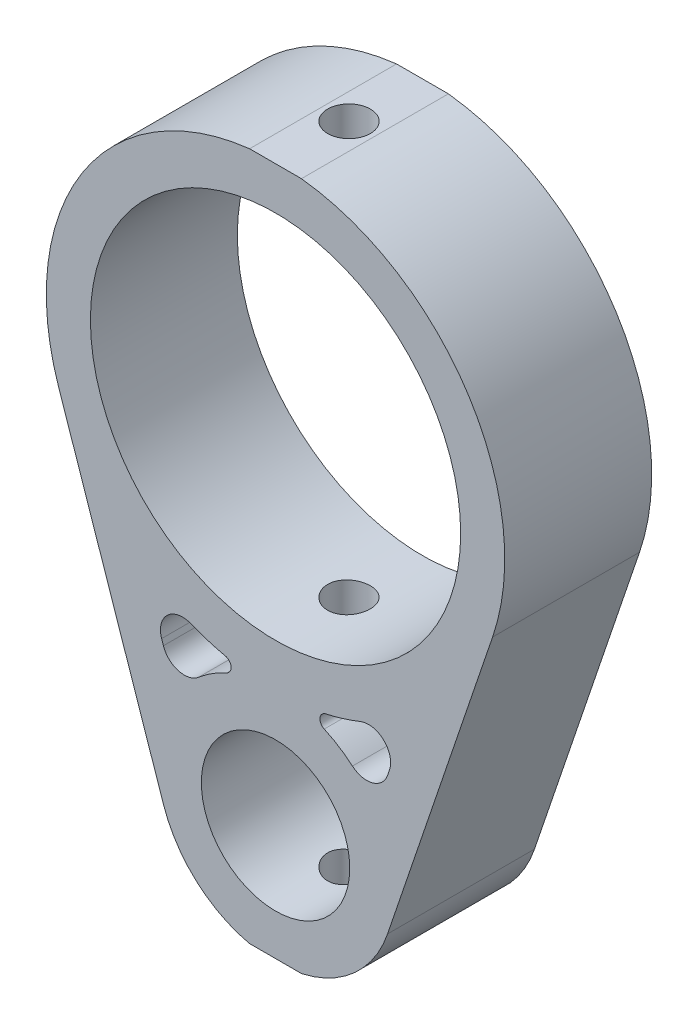
SolidWorks part; units mm, degrees
material "ABS"
ref_plane "前视基准面" through (0, 0, 0) normal (0, 0, 1) x (1, 0, 0)
ref_plane "上视基准面" through (0, 0, 0) normal (0, 1, 0) x (1, 0, 0)
ref_plane "右视基准面" through (0, 0, 0) normal (1, 0, 0) x (0, 0, -1)
sketch "草图1" plane through (0, 0, 0) normal (0, 0, 1) x (1, 0, 0)
  line L0 (0, 0) -> (0, -23.5) construction
  line L3 (-1.4149, -15.5357) -> (-1.4149, -15.5753)
  line L5 (1.4034, -15.5367) -> (1.4034, -15.5733)
  circle A0 centre (0, 0) radius 12.6
  arc A1 (1.4034, -15.5367) -> (-1.4149, -15.5357) centre (0, 0) ccw
  circle A2 centre (0, -23.5) radius 5.05
  arc A3 (-1.4149, -15.5753) -> (1.4034, -15.5733) centre (0, -23.5) ccw
  dimension "D1" = 25.2
  dimension "D2" = 3
  dimension "D3" = 10.1
  dimension "D4" = 3
  dimension "D5" = 23.5
extrude "凸台-拉伸1" add sketch "草图1" along normal blind 10
sketch "草图2" plane through (0, 0, 10) normal (0, 0, 1) x (1, 0, 0)
  line L0 (-14.773, -5.0119) -> (-7.6232, -26.0863)
  line L1 (-7.7529, -16.3662) -> (-7.6306, -16.7268)
  line L2 (0, 0) -> (0, -13.5175) construction
  line L3 (-4.1036, -15.0506) -> (-3.4583, -15.2119)
  line L4 (-14.773, -5.0119) -> (-5.3112, -13.2523)
  line L5 (-5.3112, -13.2523) -> (0, -13.5175)
  line L7 (0, -17.3992) -> (-5.929, -20.2543)
  line L8 (-5.929, -20.2543) -> (-7.6232, -26.0863)
  line L9 (5.929, -20.2543) -> (7.6232, -26.0863)
  line L10 (0, -17.3992) -> (5.929, -20.2543)
  line L11 (5.3112, -13.2523) -> (0, -13.5175)
  line L12 (14.773, -5.0119) -> (5.3112, -13.2523)
  line L13 (4.1036, -15.0506) -> (3.4583, -15.2119)
  line L14 (7.7529, -16.3662) -> (7.6306, -16.7268)
  line L15 (14.773, -5.0119) -> (7.6232, -26.0863)
  line L16 (0, -17.3992) -> (0, -23.5) construction
  circle A0 centre (0, 0) radius 15.6 construction
  circle A1 centre (0, -23.5) radius 8.05 construction
  circle A2 centre (0, 0) radius 12.6 construction
  circle A3 centre (0, -23.5) radius 5.05 construction
  arc A4 (-5.777, -14.4909) -> (-4.1036, -15.0506) centre (0, 0) ccw
  arc A5 (-5.777, -14.4909) -> (-7.7529, -16.3662) centre (-6.3325, -15.8843) ccw
  arc A6 (-3.3139, -16.1637) -> (-5.2347, -17.3844) centre (0, -23.5) ccw
  arc A7 (-7.6306, -16.7268) -> (-5.2347, -17.3844) centre (-6.2101, -16.2449) ccw
  arc A8 (-3.3139, -16.1637) -> (-3.4583, -15.2119) centre (-3.5197, -15.7081) ccw
  arc A9 (3.3139, -16.1637) -> (3.4583, -15.2119) centre (3.5197, -15.7081) cw
  arc A10 (7.6306, -16.7268) -> (5.2347, -17.3844) centre (6.2101, -16.2449) cw
  arc A11 (3.3139, -16.1637) -> (5.2347, -17.3844) centre (0, -23.5) cw
  arc A12 (5.777, -14.4909) -> (7.7529, -16.3662) centre (6.3325, -15.8843) cw
  arc A13 (5.777, -14.4909) -> (4.1036, -15.0506) centre (0, 0) cw
  arc A14 (-1.4149, -15.5753) -> (1.4034, -15.5733) centre (0, -23.5) ccw construction
  arc A15 (1.4034, -15.5367) -> (-1.4149, -15.5357) centre (0, 0) ccw construction
  point P13 (0, -15.6)
  point P21 (0, -15.45)
  point P28 (0, -15.95)
  dimension "D1" = 1.5
  dimension "D2" = 1.5
  dimension "D3" = 0.5
extrude "凸台-拉伸2" add sketch "草图2" against normal up to surface (10 mm away) up to face at (0, -11.7651, 0)
sketch "草图3" plane through (0, 0, 0) normal (0, 1, 0) x (1, 0, 0)
  line L0 (0, 0) -> (0, -10) construction
  line L1 (-15.6, -10) -> (15.6, -10) construction
  line L2 (-15.6, -5) -> (15.6, -5) construction
  line L3 (-15.6, 0) -> (-15.6, -10) construction
  line L4 (15.6, -10) -> (15.6, 0) construction
  circle A0 centre (0, -5) radius 1.45
  dimension "D1" = 2.9
extrude "切除-拉伸1" cut sketch "草图3" against normal through all both and the other way through all
sketch "草图4" plane through (0, 0, 10) normal (0, 0, 1) x (1, 0, 0)
  line L1 (-18.3524, 15.5) -> (24.7249, 15.5)
  line L2 (-18.3524, 15.5) -> (-18.3524, -31.35)
  line L3 (-18.3524, -31.35) -> (24.7249, -31.35)
  line L4 (24.7249, 15.5) -> (24.7249, -31.35)
  line L5 (-52.9005, 41.108) -> (40.9923, 41.108)
  line L6 (-52.9005, 41.108) -> (-52.9005, -39.3252)
  line L7 (-52.9005, -39.3252) -> (40.9923, -39.3252)
  line L8 (40.9923, 41.108) -> (40.9923, -39.3252)
  arc A0 (14.773, -5.0119) -> (-14.773, -5.0119) centre (0, 0) ccw construction
  arc A1 (-7.6232, -26.0863) -> (7.6232, -26.0863) centre (0, -23.5) ccw construction
  point P4 (0, 15.6)
  point P5 (0, -31.55)
  dimension "D1" = 0.2
  dimension "D2" = 0.1
extrude "切除-拉伸2" cut sketch "草图4" against normal through all both and the other way through all
